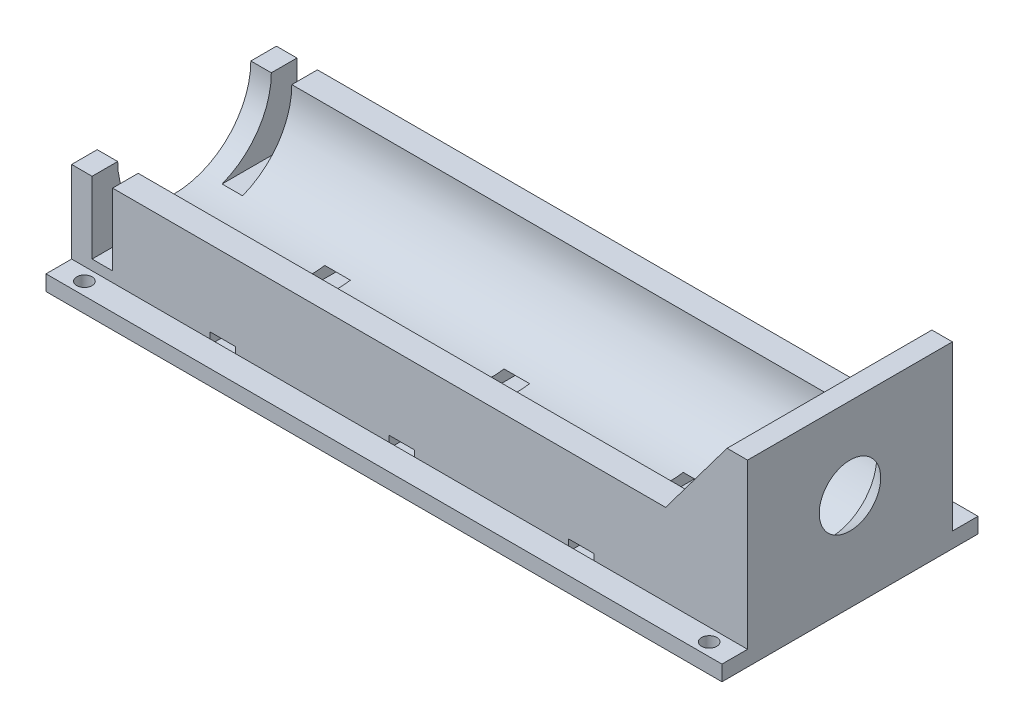
SolidWorks part; units mm, degrees
ref_plane "Front Plane" through (0, 0, 0) normal (0, 0, 1) x (1, 0, 0)
ref_plane "Top Plane" through (0, 0, 0) normal (0, 1, 0) x (1, 0, 0)
ref_plane "Right Plane" through (0, 0, 0) normal (1, 0, 0) x (0, 0, -1)
sketch "Sketch1" plane through (0, 0, 0) normal (0, 1, 0) x (1, 0, 0)
  line L1 (-64, -20) -> (64, -20)
  line L2 (-64, -20) -> (-64, 20)
  line L3 (-64, 20) -> (64, 20)
  line L4 (64, -20) -> (64, 20)
  line L5 (-64, -20) -> (64, 20) construction
  line L6 (-64, 20) -> (64, -20) construction
  point P0 (0, 0)
  dimension "D1" = 128
  dimension "D2" = 40
extrude "Boss-Extrude1" add sketch "Sketch1" along normal blind 8
sketch "Sketch2" plane through (0, 8, 0) normal (0, 1, 0) x (1, 0, 0)
  line L1 (-64, -20) -> (64, -20)
  line L2 (-64, -20) -> (-64, 20)
  line L3 (-64, 20) -> (64, 20)
  line L4 (64, -20) -> (64, 20)
extrude "Boss-Extrude2" add sketch "Sketch2" along normal blind 30
sketch "Sketch3" plane through (64, 0, 0) normal (1, 0, 0) x (0, 0, -1)
  line L3 (-15, 19) -> (-20, 19)
  line L4 (-20, 38) -> (-20, 0) construction
  line L5 (-20, 19) -> (-20, 38)
  line L6 (20, 38) -> (20, 19)
  line L7 (20, 38) -> (20, 0) construction
  line L8 (20, 19) -> (15, 19)
  line L11 (-20, 0) -> (20, 0)
  line L12 (20, 0) -> (20, 38)
  line L13 (20, 38) -> (-20, 38)
  line L14 (-20, 38) -> (-20, 0)
  line L17 (20, 38) -> (-20, 38)
  arc A0 (-15, 19) -> (15, 19) centre (0, 19) ccw
  dimension "D1" = 0
extrude "Cut-Extrude1" cut sketch "Sketch3" against normal blind 200000
sketch "Sketch5" plane through (0, 19, 0) normal (0, 1, 0) x (1, 0, 0)
  line L0 (-64, -20) -> (64, -20) construction
  line L1 (-56, -20) -> (-60, -20)
  line L2 (-56, -20) -> (-56, 20)
  line L3 (-56, 20) -> (-60, 20)
  line L4 (-60, -20) -> (-60, 20)
  line L5 (-64, 20) -> (64, 20) construction
  line L6 (-64, -20) -> (-64, -15) construction
  dimension "D1" = 4
  dimension "D2" = 4
extrude "Cut-Extrude2" cut sketch "Sketch5" against normal blind 14
sketch "Sketch6" plane through (64, 0, 0) normal (1, 0, 0) x (0, 0, -1)
  line L1 (-20, 0) -> (20, 0)
  line L2 (-20, 0) -> (-20, 35)
  line L3 (-20, 35) -> (20, 35)
  line L4 (20, 0) -> (20, 35)
  dimension "D1" = 40
  dimension "D2" = 35
extrude "Boss-Extrude3" add sketch "Sketch6" along normal blind 4
sketch "Sketch7" plane through (68, 0, 0) normal (1, 0, 0) x (0, 0, -1)
  line L0 (20, 35) -> (-20, 35) construction
  circle A0 centre (0, 19) radius 6
  dimension "D1" = 16
extrude "Cut-Extrude3" cut sketch "Sketch7" against normal blind 4 draft 39 draft outward yes
sketch "Sketch8" plane through (0, 0, -20) normal (0, 0, -1) x (-1, 0, 0)
  line L0 (-68, 0) -> (64, 0) construction
  line L1 (-38, 2) -> (-33, 2)
  line L2 (-38, 2) -> (-38, 4.2)
  line L3 (-38, 4.2) -> (-33, 4.2)
  line L4 (-33, 2) -> (-33, 4.2)
  line L5 (32, 2) -> (37, 2)
  line L6 (32, 2) -> (32, 4.2)
  line L7 (32, 4.2) -> (37, 4.2)
  line L8 (37, 2) -> (37, 4.2)
  line L9 (-3, 4.2) -> (2, 4.2)
  line L10 (-3, 4.2) -> (-3, 2)
  line L11 (-3, 2) -> (2, 2)
  line L12 (2, 4.2) -> (2, 2)
  line L13 (-68, 0) -> (-68, 35) construction
  dimension "D1" = 5
  dimension "D2" = 2.2
  dimension "D3" = 5
  dimension "D4" = 2.2
  dimension "D5" = 5
  dimension "D6" = 2.2
  dimension "D7" = 2
  dimension "D8" = 2
  dimension "D9" = 2
  dimension "D10" = 30
  dimension "D11" = 30
  dimension "D12" = 30
extrude "Cut-Extrude4" cut sketch "Sketch8" against normal blind 200
sketch "Sketch9" plane through (0, 0, 0) normal (0, -1, 0) x (1, 0, 0)
  line L2 (68, 20) -> (-64, 20)
  line L3 (68, 20) -> (68, 25)
  line L4 (68, 25) -> (-64, 25)
  line L5 (-64, 20) -> (-64, 25)
  line L6 (68, -20) -> (-64, -20)
  line L7 (68, -20) -> (68, -25)
  line L8 (68, -25) -> (-64, -25)
  line L9 (-64, -20) -> (-64, -25)
  dimension "D1" = 132
  dimension "D2" = 5
  dimension "D3" = 5
extrude "Boss-Extrude4" add sketch "Sketch9" against normal blind 3
sketch "Sketch10" plane through (0, 0, 20) normal (0, 0, 1) x (1, 0, 0)
  line L0 (68, 35) -> (68, 3) construction
  line L1 (68, 35) -> (64, 35)
  line L2 (68, 35) -> (68, 19)
  line L3 (68, 19) -> (52, 19)
  line L5 (68, 35) -> (64, 35) construction
  line L6 (-56, 19) -> (64, 19) construction
  line L7 (64, 35) -> (52, 19)
extrude "Boss-Extrude7" add sketch "Sketch10" against normal blind 3
sketch "Sketch12" plane through (0, 0, -20) normal (0, 0, -1) x (-1, 0, 0)
  line L0 (56, 19) -> (-64, 19) construction
  line L1 (-68, 35) -> (-64, 35)
  line L2 (-68, 35) -> (-68, 19)
  line L3 (-68, 19) -> (-51.9788, 19)
  line L5 (-64, 35) -> (-51.9788, 19)
extrude "Boss-Extrude9" add sketch "Sketch12" against normal blind 3
sketch "Sketch13" plane through (0, 3, 0) normal (0, 1, 0) x (1, 0, 0)
  line L1 (-64, -25) -> (-64, -20) construction
  line L2 (-64, 25) -> (68, 25) construction
  line L3 (-64, 20) -> (-64, 25) construction
  line L4 (68, -25) -> (-64, -25) construction
  line L5 (68, -20) -> (68, -25) construction
  line L6 (68, 25) -> (68, 20) construction
  circle A0 centre (-59, -22.5) radius 1.5
  circle A1 centre (-59, 22.5) radius 1.5
  circle A2 centre (63, -22.5) radius 1.5
  circle A3 centre (63, 22.5) radius 1.5
  dimension "D1" = 2.5
  dimension "D3" = 3
  dimension "D4" = 2.5
  dimension "D6" = 5
  dimension "D8" = 5
  dimension "D2" = 5
  dimension "D5" = 5
  dimension "D7" = 2.5
  dimension "D9" = 2.5
extrude "Cut-Extrude5" cut sketch "Sketch13" against normal blind 10
